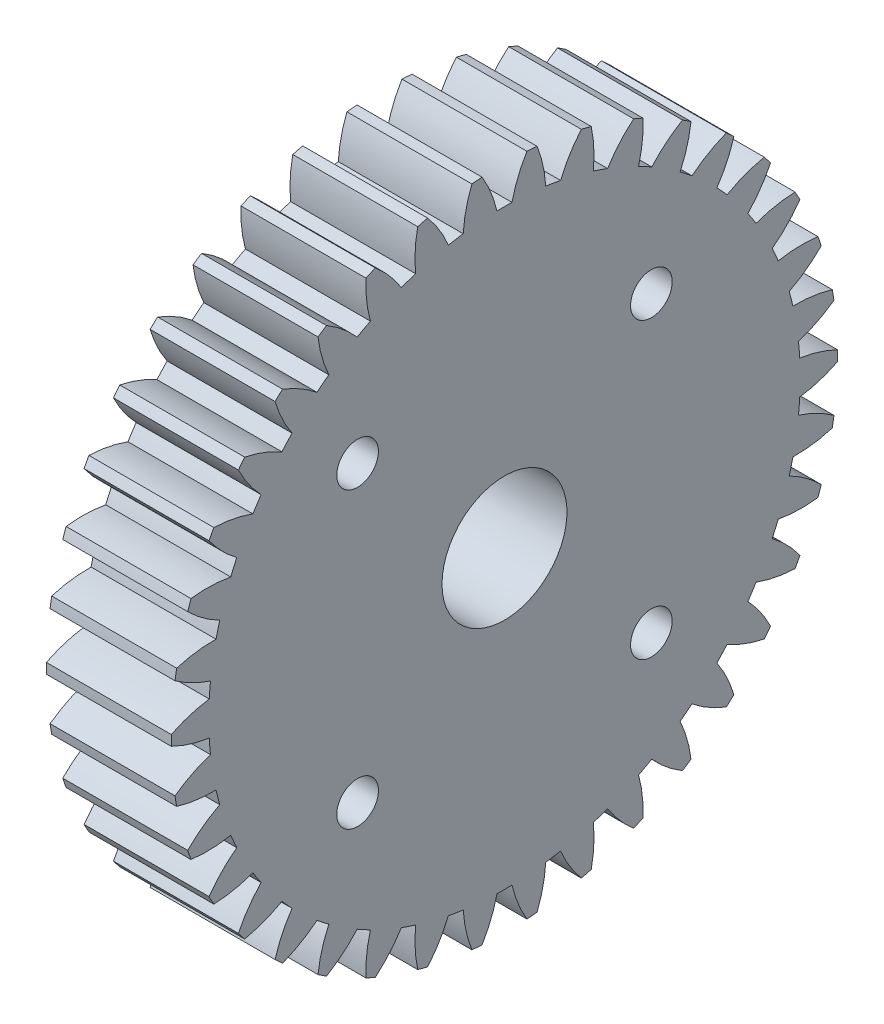
SolidWorks part; units mm, degrees
ref_plane "Plane1" through (0, 0, 0) normal (0, 0, 1) x (1, 0, 0)
ref_plane "Plane2" through (0, 0, 0) normal (0, 1, 0) x (1, 0, 0)
ref_plane "Plane3" through (0, 0, 0) normal (1, 0, 0) x (0, 0, -1)
other "Configuration Table"
sketch "HoldingSke" plane through (0, 0, 0) normal (0, 1, 0) x (1, 0, 0)
  line L0 (0, 0) -> (0.985, -0.7696)
  line L1 (-15, 0) -> (100, 0) construction
  line L2 (0, 0) -> (-2.1039, 2.3779)
  line L3 (0, 0) -> (-11.863, 4.5341)
  line L4 (0, 0) -> (6.8053, 5.3169)
  line L5 (0, 0) -> (-46.8476, -17.4728)
  line L6 (0, 0) -> (-4.9738, -3.3558)
  line L7 (-2.1039, 2.3779) -> (8.6586, 51.2059)
  line L8 (-76.2, 54.61) -> (-75.2, 54.61)
  line L9 (-71.009, 38.7566) -> (-53.1078, 45.2721)
  line L10 (-76.2, 71.12) -> (104.1128, 71.12)
  line L11 (0, 0) -> (-6, 0)
  line L12 (-76.2, 101.6) -> (-76.17, 101.6)
  line L13 (24.9733, 27.94) -> (52.9518, 28.4284)
  line L14 (24.9733, 27.94) -> (24.9743, 27.94)
  line L15 (24.9733, 27.94) -> (100.4006, 29.5858)
  line L16 (-63.627, -0.8) -> (-12.827, -0.8)
  circle A0 centre (0, 0) radius 3
  circle A1 centre (0, 0) radius 14.199
  circle A2 centre (0, 0) radius 37.5
  circle A3 centre (0, 0) radius 3
  dimension "MHD" = 28.398
  dimension "Hub_dia" = 75
  dimension "Bore" = 6
  dimension "MBD" = 6
  dimension "Num_teeth" = 38
  dimension "Pitch" = 1.25
  dimension "Overall_len" = 50
  dimension "Show_teeth" = 38
  dimension "Thickness" = 6
  dimension "OAL" = 50.0001
  dimension "T_dim" = 1
  dimension "Ap" = 20
  dimension "H" = 19.05
  dimension "Pitch_radius" = 180.3128
  dimension "Width" = 6
  dimension "Backlash" = 0.03
  dimension "Addendum_fac" = 1
  dimension "Dedendum_fac" = 1.25
  dimension "Clearance_fac" = 0.25
  dimension "Dedendum_add" = 0.001
  dimension "Module" = 0.8
sketch "BasProSke" plane through (0, 0, 0) normal (0, 1, 0) x (1, 0, 0)
  line L0 (-10, 0) -> (60, 0) construction
  line L1 (0, 0) -> (0, 16)
  line L2 (0, 0) -> (6, 0)
  line L3 (6, 0) -> (6, 16)
  line L4 (6, 16) -> (0, 16)
  dimension "Thickness" = 6
  dimension "Diameter" = 32
revolve "Base-Revolve" add sketch "BasProSke" angle 360 about L0
sketch "TooCutSke" plane through (0, 0, 0) normal (1, 0, 0) x (0, 0, -1)
  line L1 (0, 0) -> (0, 107) construction
  line L2 (0, 0) -> (-0.6806, 15.1848) construction
  line L3 (0, 0) -> (-2.5086, 30.2744) construction
  line L4 (-0.6806, 15.1848) -> (-1.2543, 15.1372) construction
  arc A0 (0.3605, 14.1944) -> (-0.3605, 14.1944) centre (0, 0) ccw
  arc A1 (1.0914, 15.9882) -> (-1.0914, 15.9882) centre (0, 0) ccw
  circle A2 centre (0, 0) radius 15.2 construction
  circle A3 centre (0, 0) radius 14.2833 construction
  arc A4 (-0.3605, 14.1944) -> (-1.0914, 15.9882) centre (-6.2846, 12.8264) ccw
  arc A5 (1.0914, 15.9882) -> (0.3605, 14.1944) centre (6.2846, 12.8264) ccw
  dimension "Root_dia" = 28.398
  dimension "Overcut_dia" = 32.0508
  dimension "Pitch_dia" = 30.4
  dimension "Base_dia" = 28.5667
  dimension "Flank_rad" = 6.08
  dimension "Half_ang" = 4.737
  dimension "Half_CT" = 0.5756
extrude "ToothCut" cut sketch "TooCutSke" along normal through all
fillet "Breaks" [suppressed] radius 0.016
fillet "RootFillets" [suppressed] radius 0.201
pattern_circular "TeethCuts" count 38 every 9.474 about axis through (-10, 0, 0) along (1, 0, 0) of "ToothCut", "RootFillets", "Breaks"
sketch "HubNeaOneSke" plane through (0, 0, 0) normal (-1, 0, 0) x (0, 0, 1)
  circle A0 centre (0, 0) radius 14.199
  dimension "Diameter" = 28.398
extrude "HubNearOne" [suppressed] add sketch "HubNeaOneSke" along normal blind 44.0001
sketch "HubNeaBotSke" plane through (0, 0, 0) normal (-1, 0, 0) x (0, 0, 1)
  circle A0 centre (0, 0) radius 14.199
  dimension "Diameter" = 28.398
extrude "HubNearBoth" [suppressed] add sketch "HubNeaBotSke" along normal blind 22
ref_plane "FarPln" through (6, 0, 0) normal (1, 0, 0) x (0, 0, -1)
sketch "HubFarSke" plane through (6, 0, 0) normal (1, 0, 0) x (0, 0, -1)
  circle A0 centre (0, 0) radius 14.199
  dimension "Diameter" = 28.398
extrude "HubFar" [suppressed] add sketch "HubFarSke" along normal blind 22
sketch "BorSke" plane through (0, 0, 0) normal (1, 0, 0) x (0, 0, -1)
  circle A0 centre (0, 0) radius 3
  dimension "Diameter" = 6
extrude "Bore" cut sketch "BorSke" along normal mid plane 100.0001
sketch "KeySke" plane through (0, 0, 0) normal (1, 0, 0) x (0, 0, -1)
  line L0 (-1, 0) -> (-1, 4)
  line L1 (-1, 4) -> (1, 4)
  line L2 (1, 4) -> (1, 0)
  line L3 (0, 0) -> (0, 34) construction
  line L4 (-1, 0) -> (1, 0)
  dimension "Offset" = 4
  dimension "Width" = 2
extrude "Keyway" [suppressed] cut sketch "KeySke" along normal mid plane 100.0001
pattern_circular "Keyway2" [suppressed] count 2 every 90 about axis through (-10, 0, 0) along (1, 0, 0)
sketch "Sketch1" plane through (6, 0, 0) normal (1, 0, 0) x (0, 0, -1)
  circle A0 centre (-7.0534, 7.0534) radius 1
  circle A1 centre (7.0534, 7.0533) radius 1
  circle A5 centre (7.0533, -7.0534) radius 1
  circle A6 centre (-7.0534, -7.0533) radius 1
  point P12 (-1.0184, 0)
  point P13 (0, 0)
  dimension "D1" = 2
  dimension "D2" = 7.0534
  dimension "D3" = 7.0534
  dimension "D4" = 4
extrude "Cut-Extrude1" cut sketch "Sketch1" against normal blind 10
equation "' \"Module@HoldingSke\" = 6.35"
equation "' \"Num_teeth@HoldingSke\" = 12"
equation "' \"Ap@HoldingSke\" =  20"
equation "' \"Ap@HoldingSke\" = 20"
equation "' \"Width@HoldingSke\" = 0.5 * 25.4"
equation "' \"Hub_dia@HoldingSke\"= 1 * 25.4"
equation "' \"Hub_dia@HoldingSke\" = 1 * 25.4"
equation "' \"Overall_len@HoldingSke\" = 1.0 * 25.4"
equation "' \"Bore@HoldingSke\" = 0.75 * 25.4"
equation "' \"T_dim@HoldingSke\" = 0.1 * 25.4"
equation "' \"Width@KeySke\" = 0.25 * 25.4"
equation "' \"Show_teeth@HoldingSke\" = 13"
equation "' \"Backlash@HoldingSke\" = 0.009 * 25.4"
equation "' \"Addendum_fac@HoldingSke\" = 1.0"
equation "' \"Dedendum_fac@HoldingSke\" = 1.25"
equation "' \"Dedendum_add@HoldingSke\" = 0.00005 * 25.4"
equation "' \"Clearance_fac@HoldingSke\" = 0.25"
equation "\"Pitch@HoldingSke\" = 1 / \"Module@HoldingSke\""
equation "\"Overcut_dia@TooCutSke\" = (\"Num_teeth@HoldingSke\" + 2 * \"Addendum_fac@HoldingSke\") / \"Pitch@HoldingSke\" + 0.002 * 25.4"
equation "\"Pitch_dia@TooCutSke\" = \"Num_teeth@HoldingSke\" / \"Pitch@HoldingSke\""
equation "\"Base_dia@TooCutSke\" = \"Num_teeth@HoldingSke\" / \"Pitch@HoldingSke\" * cos((\"Ap@HoldingSke\"  * 3.14159265 / 180))"
equation "\"Root_dia@TooCutSke\" = (\"Num_teeth@HoldingSke\" + 2) / \"Pitch@HoldingSke\" - 2 * (\"Addendum_fac@HoldingSke\" + \"Dedendum_fac@HoldingSke\") / \"Pitch@HoldingSke\" - \"Dedendum_add@HoldingSke\" * 2"
equation "\"Half_ang@TooCutSke\" = 180 / \"Num_teeth@HoldingSke\""
equation "\"Half_CT@TooCutSke\" = \"Num_teeth@HoldingSke\" / \"Pitch@HoldingSke\" * sin((3.14159265 / 2 / \"Num_teeth@HoldingSke\")) / 2 - 7 * \"Backlash@HoldingSke\" / 4"
equation "\"Flank_rad@TooCutSke\" = \"Num_teeth@HoldingSke\" / \"Pitch@HoldingSke\" / 5"
equation "\"Radius@RootFillets\" = \"Clearance_fac@HoldingSke\" / \"Pitch@HoldingSke\" + \"Dedendum_add@HoldingSke\""
equation "\"Break_rad@Breaks\" = 0.02 / \"Pitch@HoldingSke\""
equation "\"Thickness@HoldingSke\" = \"Width@HoldingSke\""
equation "\"OAL@HoldingSke\" = \"Thickness@HoldingSke\""
equation "\"MHD@HoldingSke\" = (\"Num_teeth@HoldingSke\" + 2) / \"Pitch@HoldingSke\" - 2 * (\"Addendum_fac@HoldingSke\" + \"Dedendum_fac@HoldingSke\")  / \"Pitch@HoldingSke\" - \"Dedendum_add@HoldingSke\" * 2"
equation "\"MBD@HoldingSke\" = (\"Num_teeth@HoldingSke\" + 2) / \"Pitch@HoldingSke\" - 2 * (\"Addendum_fac@HoldingSke\" + \"Dedendum_fac@HoldingSke\")  / \"Pitch@HoldingSke\" - \"Dedendum_add@HoldingSke\" * 2 - 0.002 * 25.4"
equation "\"MHD@HoldingSke\" = ((sgn( \"MHD@HoldingSke\" - \"Hub_dia@HoldingSke\" )-1)*( \"MHD@HoldingSke\" - \"Hub_dia@HoldingSke\" ))/-2+ \"Hub_dia@HoldingSke\""
equation "\"MBD@HoldingSke\" = ((sgn( \"MBD@HoldingSke\" - \"Bore@HoldingSke\" )-1)*( \"MBD@HoldingSke\" - \"Bore@HoldingSke\" ))/-2+ \"Bore@HoldingSke\""
equation "\"OAL@HoldingSke\" = ((sgn( \"OAL@HoldingSke\" - \"Overall_len@HoldingSke\" )+1)*( \"OAL@HoldingSke\" - \"Overall_len@HoldingSke\" ))/2 + \"Overall_len@HoldingSke\" + 0.000002 * 25.4"
equation "\"Num_teeth@TeethCuts\" = int( \"Show_teeth@HoldingSke\" ) + 1"
equation "\"Num_teeth@TeethCuts\" = ((sgn( \"Num_teeth@TeethCuts\" - \"Num_teeth@HoldingSke\" )-1)*( \"Num_teeth@TeethCuts\" - \"Num_teeth@HoldingSke\" ))/-2+ \"Num_teeth@HoldingSke\""
equation "\"Num_teeth@TeethCuts\" = ((sgn( \"Num_teeth@TeethCuts\" - 2.0)+1)*( \"Num_teeth@TeethCuts\" - 2.0))/2 +2.0"
equation "\"Angle@TeethCuts\" = 360.0 / \"Num_teeth@HoldingSke\""
equation "\"Diameter@BasProSke\" = (\"Num_teeth@HoldingSke\" + 2 * \"Addendum_fac@HoldingSke\") / \"Pitch@HoldingSke\""
equation "\"Thickness@BasProSke\"  = \"Thickness@HoldingSke\""
equation "' \"Fillet_rad@BasProSke\" =  \"Thickness@HoldingSke\" * 0.05"
equation "' \"Fillet_rad@BasProSke\" = \"Thickness@HoldingSke\" * 0.05"
equation "\"MHD@HoldingSke\" = ((sgn( \"MHD@HoldingSke\" - \"Root_dia@TooCutSke\" )-1)*( \"MHD@HoldingSke\" - \"Root_dia@TooCutSke\" ))/-2+ \"Root_dia@TooCutSke\""
equation "\"Diameter@HubNeaOneSke\" = \"MHD@HoldingSke\""
equation "\"Length@HubNearOne\" = \"OAL@HoldingSke\" - \"Thickness@BasProSke\""
equation "\"Diameter@HubNeaBotSke\" = \"MHD@HoldingSke\""
equation "\"Length@HubNearBoth\" = ( \"OAL@HoldingSke\" - \"Thickness@BasProSke\" ) / 2.0"
equation "\"Thickness@FarPln\" = \"Thickness@BasProSke\""
equation "\"Diameter@HubFarSke\" = \"MHD@HoldingSke\""
equation "\"Length@HubFar\" = ( \"OAL@HoldingSke\" - \"Thickness@BasProSke\" ) / 2.0"
equation "\"Diameter@BorSke\" = \"MBD@HoldingSke\""
equation "\"D1@Bore\" = \"OAL@HoldingSke\" * 2.0"
equation "\"D1@Keyway\" = \"OAL@HoldingSke\" * 2.0"
equation "\"Offset@KeySke\" = \"T_dim@HoldingSke\" + \"MBD@HoldingSke\" / 2.0"
